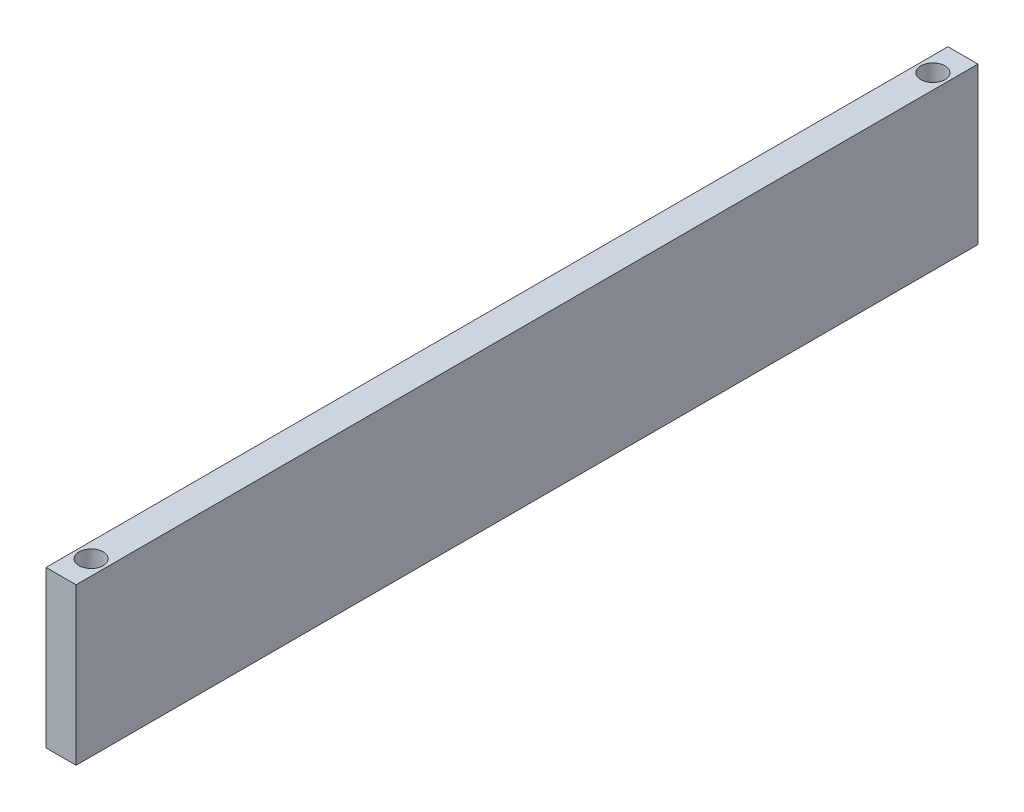
SolidWorks part; units mm, degrees
other "Markup1"
sketch "Sketch6" plane through (0, 0, 0) normal (0.7258, -0.6292, 0.2781) x (-0.261, -0.6259, -0.735)
ref_plane "Front Plane" through (0, 0, 0) normal (0, 0, 1) x (1, 0, 0)
ref_plane "Top Plane" through (0, 0, 0) normal (0, 1, 0) x (1, 0, 0)
ref_plane "Right Plane" through (0, 0, 0) normal (1, 0, 0) x (0, 0, -1)
sketch "Sketch1" plane through (0, 0, 0) normal (0, 0, 1) x (1, 0, 0)
  line L1 (-6.35, 0) -> (-6.35, 33.02)
  line L2 (-6.35, 33.02) -> (0, 33.02)
  line L3 (0, 33.02) -> (0, 0)
  line L6 (-6.35, 0) -> (0, 0)
  dimension "D3" = 6.35
  dimension "D4" = 33.02
extrude "Boss-Extrude1" add sketch "Sketch1" against normal blind 190.5
sketch "Sketch2" plane through (-6.35, 0, 0) normal (-1, 0, 0) x (0, 0, 1)
  line L0 (-190.5, 33.02) -> (-190.5, 0) construction
  circle A1 centre (-160.5, 16.51) radius 3.175
  point P5 (-190.5, 16.51)
  dimension "D1" = 6.35
  dimension "D2" = 30
extrude "Cut-Extrude1" [suppressed] cut sketch "Sketch2" against normal up to next
sketch "Sketch3" plane through (0, 33.02, 0) normal (0, 1, 0) x (1, 0, 0)
  line L0 (-3.175, 190.5) -> (-3.175, 0) construction
  line L1 (0, 190.5) -> (-6.35, 190.5) construction
  line L2 (0, 0) -> (-6.35, 0) construction
  circle A0 centre (-3.175, 6.35) radius 2.54
  circle A1 centre (-3.175, 184.15) radius 2.54
  dimension "D1" = 5.08
  dimension "D3" = 6.35
  dimension "D2" = 6.35
extrude "Cut-Extrude2" cut sketch "Sketch3" against normal through all
sketch "Sketch4" plane through (0, 0, 0) normal (0, -1, 0) x (1, 0, 0)
  line L0 (-9.525, 0) -> (-9.525, -381) construction
  line L1 (-12.7, 0) -> (0, 0) construction
  line L2 (-12.7, -381) -> (0, -381) construction
  line L3 (0, -381) -> (0, 0) construction
  circle A0 centre (-9.525, -374.65) radius 2.54
  circle A1 centre (-9.525, -6.35) radius 2.54
  dimension "D2" = 5.08
  dimension "D1" = 9.525
  dimension "D3" = 6.35
  dimension "D4" = 6.35
sketch "Sketch5" plane through (0, 0, -190.5) normal (0, 0, -1) x (-1, 0, 0)
  line L1 (6.35, 6.35) -> (0, 6.35)
  line L2 (6.35, 6.35) -> (6.35, 0)
  line L3 (6.35, 0) -> (0, 0)
  line L4 (0, 6.35) -> (0, 0)
